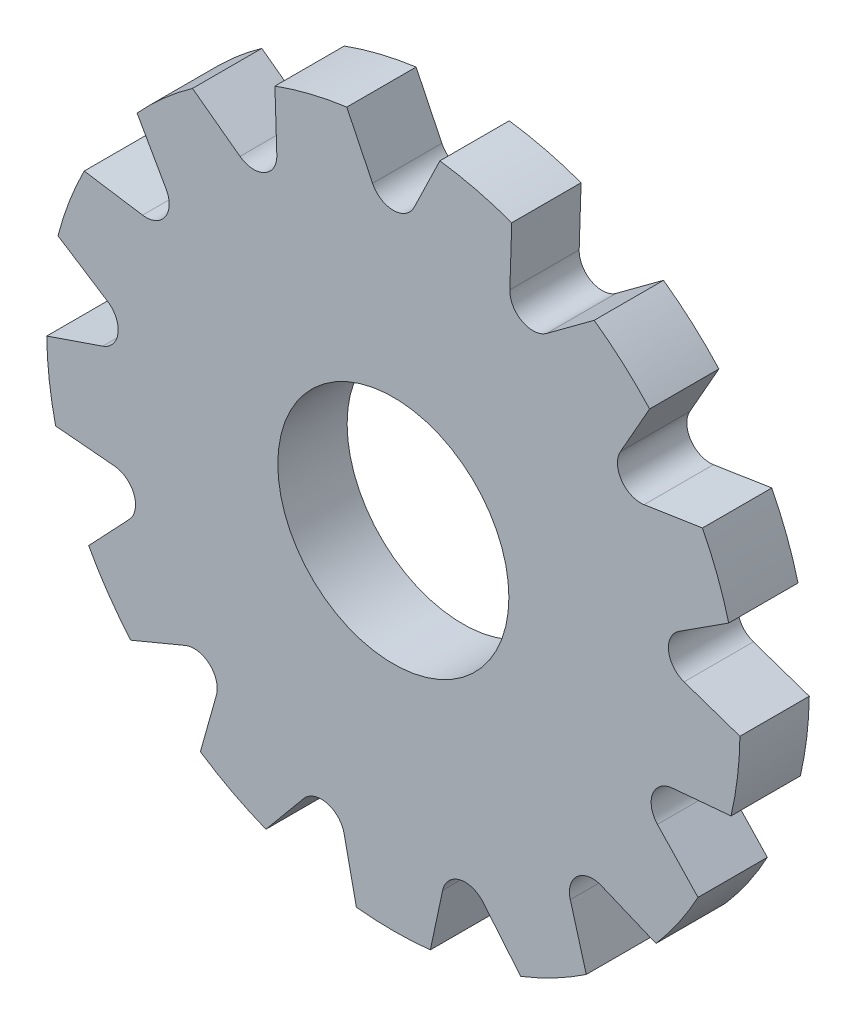
SolidWorks part; units mm, degrees
ref_plane "Front Plane" through (0, 0, 0) normal (0, 0, 1) x (1, 0, 0)
ref_plane "Top Plane" through (0, 0, 0) normal (0, 1, 0) x (1, 0, 0)
ref_plane "Right Plane" through (0, 0, 0) normal (1, 0, 0) x (0, 0, -1)
sketch "Sketch1" plane through (0, 0, 0) normal (0, 0, 1) x (1, 0, 0)
  circle A0 centre (0, 0) radius 30
  circle A1 centre (0, 0) radius 10
  dimension "D1" = 20
  dimension "D2" = 60
extrude "Boss-Extrude1" add sketch "Sketch1" along normal blind 6
sketch "Sketch2" plane through (0, 0, 6) normal (0, 0, 1) x (1, 0, 0)
  line L2 (0, 30) -> (0, 36.5546) construction
  line L3 (-4.0287, 29.7283) -> (-1.7999, 25.128)
  line L4 (4.0287, 29.7283) -> (1.7999, 25.128)
  circle A6 centre (0, 0) radius 30 construction
  arc A7 (4.0287, 29.7283) -> (-4.0287, 29.7283) centre (0, 0) ccw
  arc A8 (-1.7999, 25.128) -> (1.7999, 25.128) centre (0, 26) ccw
  dimension "D1" = 4
  dimension "D2" = 4
  dimension "D3" = 25.85
  dimension "D4" = 25.85
extrude "Cut-Extrude1" cut sketch "Sketch2" against normal blind 6
pattern_circular "CirPattern1" count 13 over 360 about axis through (0, 0, 0) along (0, 0, 1) of "Cut-Extrude1"
ref_plane "Plane1" through (0, 0, 3) normal (0, 0, 1) x (1, 0, 0)
